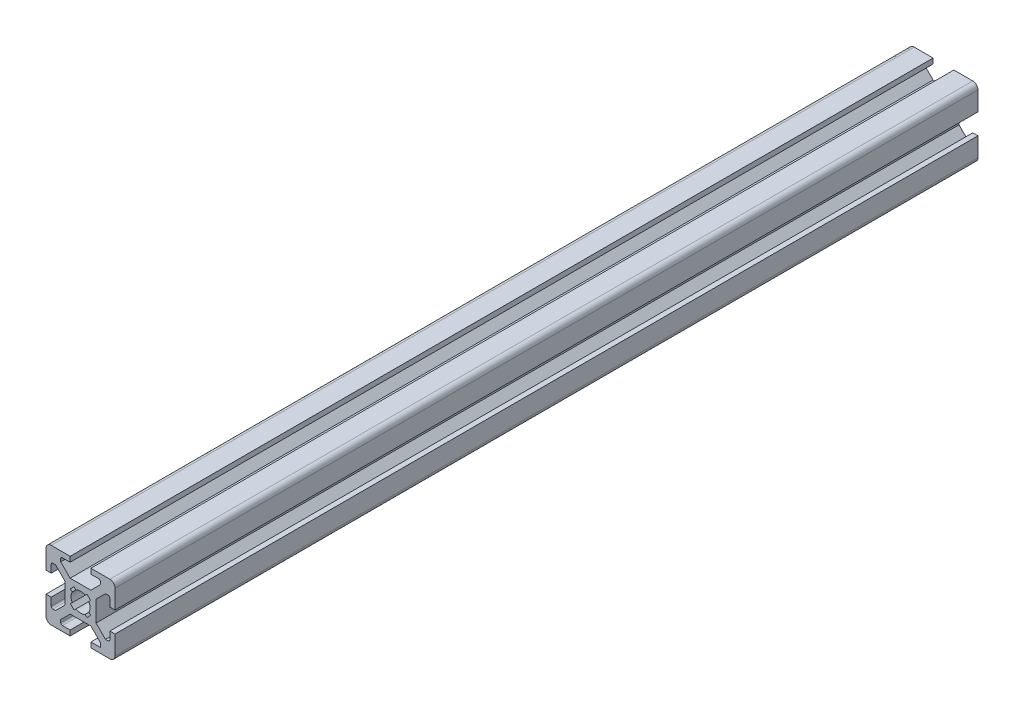
SolidWorks part; units mm, degrees
ref_plane "Alzado" through (0, 0, 0) normal (0, 0, 1) x (1, 0, 0)
ref_plane "Planta" through (0, 0, 0) normal (0, 1, 0) x (1, 0, 0)
ref_plane "Vista lateral" through (0, 0, 0) normal (1, 0, 0) x (0, 0, -1)
other "Tabla de configuración"
sketch "Croquis1" plane through (0, 0, 0) normal (0, 0, 1) x (1, 0, 0)
  line L0 (3, -4.5) -> (5.7414, -7.2414)
  line L1 (-10, 10) -> (-3, 10)
  line L2 (-10, 10) -> (-10, 3)
  line L3 (-10, -10) -> (-3, -10)
  line L4 (10, 10) -> (10, 3)
  line L5 (-10, 10) -> (10, -10) construction
  line L6 (-10, -10) -> (10, 10) construction
  line L7 (-3, 4.5) -> (3, 4.5)
  line L8 (-4.5, 3) -> (-4.5, -3)
  line L9 (-3, -4.5) -> (3, -4.5)
  line L10 (4.5, 3) -> (4.5, -3)
  line L11 (-4.5, 4.5) -> (4.5, -4.5) construction
  line L12 (-4.5, -4.5) -> (4.5, 4.5) construction
  line L13 (5.7414, -7.2414) -> (5.7414, -8.5)
  line L14 (5.7414, -8.5) -> (3, -8.5)
  line L15 (3, -8.5) -> (3, -10)
  line L16 (-7.2414, 5.7414) -> (-4.5, 3)
  line L17 (-3, -10) -> (-3, -8.5)
  line L18 (-3, -8.5) -> (-5.7414, -8.5)
  line L19 (-5.7414, -8.5) -> (-5.7414, -7.2414)
  line L20 (-5.7414, -7.2414) -> (-3, -4.5)
  line L21 (0, -4.5) -> (0, -10) construction
  line L22 (3, -10) -> (10, -10)
  line L24 (-4.5, -3) -> (-7.2414, -5.7414)
  line L25 (-7.2414, -5.7414) -> (-8.5, -5.7414)
  line L26 (-8.5, -5.7414) -> (-8.5, -3)
  line L27 (-8.5, -3) -> (-10, -3)
  line L28 (-10, 3) -> (-8.5, 3)
  line L29 (-8.5, 3) -> (-8.5, 5.7414)
  line L30 (-8.5, 5.7414) -> (-7.2414, 5.7414)
  line L31 (5.7414, 7.2414) -> (3, 4.5)
  line L33 (-3, 4.5) -> (-5.7414, 7.2414)
  line L34 (-5.7414, 7.2414) -> (-5.7414, 8.5)
  line L35 (-5.7414, 8.5) -> (-3, 8.5)
  line L36 (-3, 8.5) -> (-3, 10)
  line L37 (3, 10) -> (3, 8.5)
  line L38 (3, 8.5) -> (5.7414, 8.5)
  line L39 (5.7414, 8.5) -> (5.7414, 7.2414)
  line L40 (7.2414, -5.7414) -> (4.5, -3)
  line L42 (4.5, 3) -> (7.2414, 5.7414)
  line L43 (7.2414, 5.7414) -> (8.5, 5.7414)
  line L44 (8.5, 5.7414) -> (8.5, 3)
  line L45 (8.5, 3) -> (10, 3)
  line L46 (10, -3) -> (8.5, -3)
  line L47 (8.5, -3) -> (8.5, -5.7414)
  line L48 (8.5, -5.7414) -> (7.2414, -5.7414)
  line L49 (3, 10) -> (10, 10)
  line L50 (-10, -3) -> (-10, -10)
  line L51 (10, -3) -> (10, -10)
  line L52 (3, 4.5) -> (-3, 4.5) [skipped]
  line L53 (-4.5, 3) -> (-4.5, -3) [skipped]
  line L54 (4.5, -3) -> (4.5, 3) [skipped]
  point P0 (0, 0)
  point P6 (0, 0)
  point P26 (0, 0)
  point P37 (0, 0)
  point P48 (0, 0)
  point P59 (0, 0)
  dimension "D1" = 20
  dimension "D2" = 1.5
  dimension "D3" = 9
  dimension "D4" = 7
  dimension "D5" = 6
  dimension "D6" = 4
  dimension "D7" = 5.5
extrude "Saliente-Extruir1" add sketch "Croquis1" along normal blind 250
fillet "Redondeo1" radius 1.5 4 edges at (10, -10, 125) (-10, -10, 125) (10, 10, 125) (-10, 10, 125)
fillet "Redondeo2" radius 0.5 7 edges at (-5.7414, -8.5, 125) (5.7414, 8.5, 125) (-5.7414, 8.5, 125) (8.5, -5.7414, 125) (-8.5, -5.7414, 125) (8.5, 5.7414, 125) (-8.5, 5.7414, 125)
sketch "Croquis2" plane through (0, 0, 0) normal (0, 0, -1) x (-1, 0, 0)
  line L0 (-1.3405, 2.4012) -> (-1.8708, 2.9315)
  line L1 (-1.8708, 2.9315) -> (-2.9315, 1.8708)
  line L2 (-2.9315, 1.8708) -> (-2.4012, 1.3405)
  line L3 (-4.5, 3) -> (-7.2414, 5.7414) construction
  line L5 (1.8708, 2.9315) -> (1.3405, 2.4012)
  line L6 (2.9315, 1.8708) -> (1.8708, 2.9315)
  line L7 (2.4012, 1.3405) -> (2.9315, 1.8708)
  line L8 (2.9315, -1.8708) -> (2.4012, -1.3405)
  line L9 (1.8708, -2.9315) -> (2.9315, -1.8708)
  line L10 (1.3405, -2.4012) -> (1.8708, -2.9315)
  line L11 (-1.8708, -2.9315) -> (-1.3405, -2.4012)
  line L12 (-2.9315, -1.8708) -> (-1.8708, -2.9315)
  line L13 (-2.4012, -1.3405) -> (-2.9315, -1.8708)
  arc A0 (-2.4012, 1.3405) -> (-2.4012, -1.3405) centre (0, 0) ccw
  arc A1 (-1.3405, -2.4012) -> (1.3405, -2.4012) centre (0, 0) ccw
  arc A2 (2.4012, -1.3405) -> (2.4012, 1.3405) centre (0, 0) ccw
  arc A3 (1.3405, 2.4012) -> (-1.3405, 2.4012) centre (0, 0) ccw
  point P25 (0, 0)
  dimension "D1" = 5.5
  dimension "D2" = 0.75
  dimension "D3" = 1.5
  dimension "D4" = 4
extrude "Cortar-Extruir1" cut sketch "Croquis2" against normal through all
